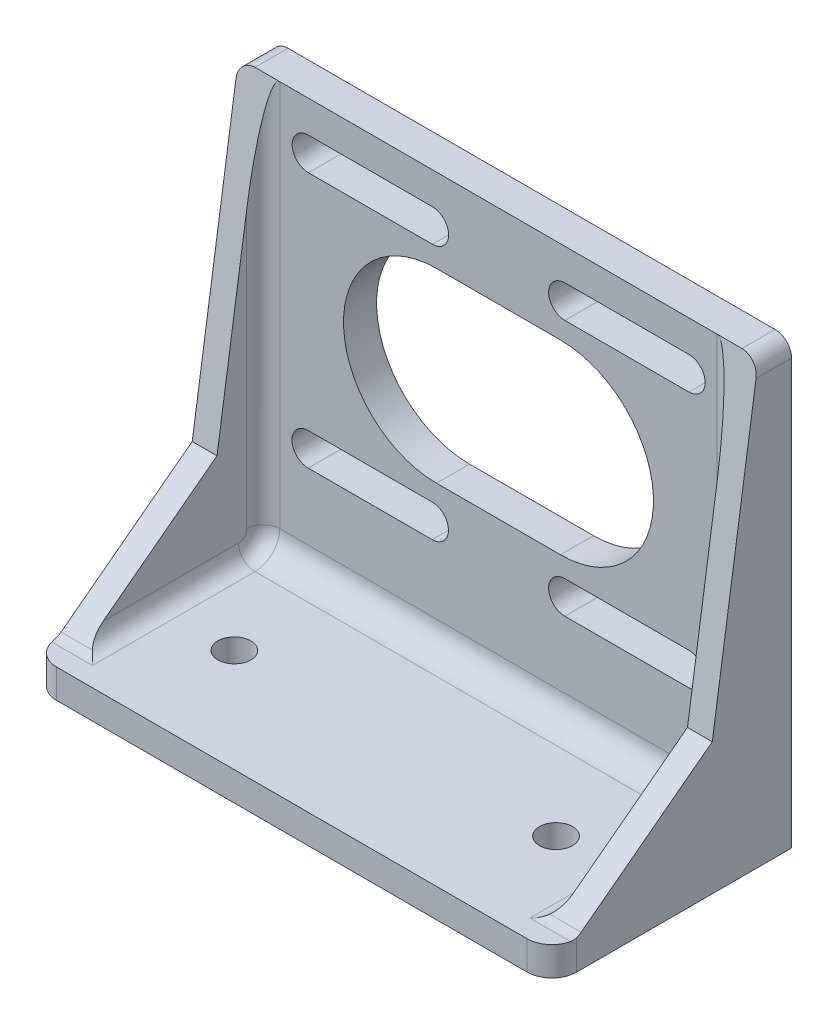
SolidWorks part; units mm, degrees
ref_plane "Front" through (0, 0, 0) normal (0, 0, 1) x (1, 0, 0)
ref_plane "Top" through (0, 0, 0) normal (0, 1, 0) x (1, 0, 0)
ref_plane "Right" through (0, 0, 0) normal (1, 0, 0) x (0, 0, -1)
sketch "Эскиз1" plane through (0, 0, 0) normal (0, 0, 1) x (1, 0, 0)
  line L0 (-7.5, 11.25) -> (7.5, 11.25)
  line L1 (-7.5, -11.25) -> (7.5, -11.25)
  line L3 (-31.4611, 21.3419) -> (-31.4611, -32)
  line L4 (-31.4611, -32) -> (31.4611, -32)
  line L5 (31.4611, 21.3419) -> (31.4611, -32)
  line L8 (-23, 15.5) -> (-8, 15.5) construction
  line L9 (-23, 17.4687) -> (-8, 17.4687)
  line L10 (-23, 13.5313) -> (-8, 13.5313)
  line L11 (8.036, 15.5375) -> (23.036, 15.5375) construction
  line L12 (8.036, 17.5062) -> (23.036, 17.5062)
  line L13 (8.036, 13.5689) -> (23.036, 13.5689)
  line L14 (-23.0223, -15.4597) -> (-8.0223, -15.4597) construction
  line L15 (-23.0223, -13.491) -> (-8.0223, -13.491)
  line L16 (-23.0223, -17.4284) -> (-8.0223, -17.4284)
  line L17 (8.0289, -15.4584) -> (23.0289, -15.4584) construction
  line L18 (8.0289, -13.4897) -> (23.0289, -13.4897)
  line L19 (8.0289, -17.4271) -> (23.0289, -17.4271)
  line L20 (-31.4611, 21.3419) -> (31.4611, 21.3419)
  arc A0 (-7.5, 11.25) -> (-7.5, -11.25) centre (-7.5, 0) ccw
  arc A1 (7.5, 11.25) -> (7.5, -11.25) centre (7.5, 0) cw
  arc A2 (-23, 17.4687) -> (-23, 13.5313) centre (-23, 15.5) ccw
  arc A3 (-8, 13.5313) -> (-8, 17.4687) centre (-8, 15.5) ccw
  arc A4 (8.036, 17.5062) -> (8.036, 13.5689) centre (8.036, 15.5375) ccw
  arc A5 (23.036, 13.5689) -> (23.036, 17.5062) centre (23.036, 15.5375) ccw
  arc A6 (-23.0223, -13.491) -> (-23.0223, -17.4284) centre (-23.0223, -15.4597) ccw
  arc A7 (-8.0223, -17.4284) -> (-8.0223, -13.491) centre (-8.0223, -15.4597) ccw
  arc A8 (8.0289, -13.4897) -> (8.0289, -17.4271) centre (8.0289, -15.4584) ccw
  arc A9 (23.0289, -17.4271) -> (23.0289, -13.4897) centre (23.0289, -15.4584) ccw
  point P8 (-15.5, 15.5)
  point P15 (15.536, 15.5375)
  point P22 (-15.5223, -15.4597)
  point P29 (15.5289, -15.4584)
  point P34 (0, 0)
  dimension "D2" = 11.25
extrude "Бобышка-Вытянуть1" add sketch "Эскиз1" along normal blind 4
sketch "Эскиз2" plane through (0, 0, 4) normal (0, 0, 1) x (1, 0, 0)
  line L0 (31.4611, -32) -> (31.4611, 21.3419) construction
  line L1 (-31.4611, -32) -> (31.4611, -32)
  line L2 (-31.4611, -32) -> (-31.4611, -28.5)
  line L3 (-31.4611, -28.5) -> (31.4611, -28.5)
  line L4 (31.4611, -32) -> (31.4611, -28.5)
  dimension "D1" = 3.5
extrude "Бобышка-Вытянуть2" add sketch "Эскиз2" along normal blind 25
sketch "Эскиз3" plane through (0, -28.5, 0) normal (0, 1, 0) x (1, 0, 0)
  line L9 (-31.4611, -16.5) -> (31.4611, -16.5) construction
  line L10 (-31.4611, -29) -> (-31.4611, -4) construction
  line L11 (31.4611, -29) -> (31.4611, -4) construction
  circle A4 centre (-19.4611, -16.5) radius 2
  circle A5 centre (19.4611, -16.5) radius 2
  dimension "D6" = 12
  dimension "12" = 12
extrude "Вырез-Вытянуть1" cut sketch "Эскиз3" against normal up to next
fillet "Скругление1" radius 3 3 edges at (0, -28.5, 4) (31.4611, -30.25, 29) (-31.4611, -30.25, 29)
sketch "Эскиз4" plane through (31.4611, 0, 0) normal (1, 0, 0) x (0, 0, -1)
  line L0 (-26, -28.5) -> (-4, -28.5)
  line L1 (-4, -28.5) -> (-4, 21.3419)
  line L3 (-4, 21.3419) -> (-9.5959, -16.0661)
  line L4 (-9.5959, -16.0661) -> (-26, -28.5)
extrude "Бобышка-Вытянуть3" add sketch "Эскиз4" against normal blind 3
sketch "Эскиз5" plane through (-31.4611, 0, 0) normal (-1, 0, 0) x (0, 0, 1)
  line L0 (26, -28.5) -> (4, -28.5)
  line L1 (4, -28.5) -> (4, 21.3419)
  line L3 (4, 21.3419) -> (9.5959, -16.0661)
  line L4 (9.5959, -16.0661) -> (26, -28.5) construction
  line L5 (9.5959, -16.0661) -> (26, -28.5)
extrude "Бобышка-Вытянуть4" add sketch "Эскиз5" against normal blind 3
fillet "Скругление2" radius 2 10 edges at (28.4611, -2.079, 4) (28.4611, -27.6213, 4.8787) (-28.4611, -2.079, 4) (-28.4611, -27.6213, 4.8787) (28.4611, -28.5, 16.5) (-28.4611, -28.5, 16.5) (31.4611, 21.3419, 2) (-31.4611, 21.3419, 2) (29.9611, -28.5, 26) (-29.9611, -28.5, 26)
